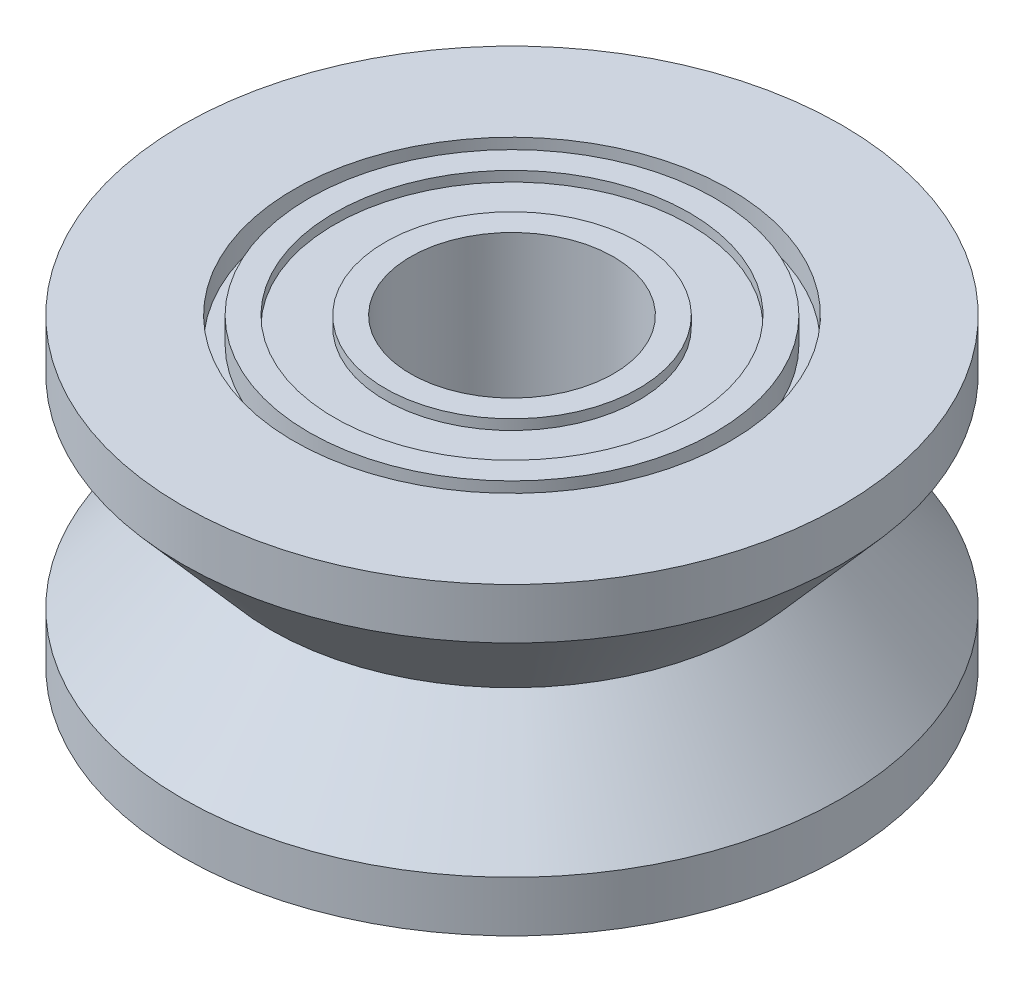
SolidWorks part; units mm, degrees
material "AISI 304"
ref_plane "Front Plane" through (0, 0, 0) normal (0, 0, 1) x (1, 0, 0)
ref_plane "Top Plane" through (0, 0, 0) normal (0, 1, 0) x (1, 0, 0)
ref_plane "Right Plane" through (0, 0, 0) normal (1, 0, 0) x (0, 0, -1)
sketch "Sketch1" plane through (0, 0, 0) normal (0, 0, 1) x (1, 0, 0)
  line L0 (-6.5, 3) -> (-6.5, 2)
  line L1 (-6.5, 2) -> (-4.75, 0)
  line L2 (-4.75, 0) -> (-6.5, -2)
  line L3 (-6.5, -2) -> (-6.5, -3)
  line L4 (-6.5, -3) -> (-2, -3)
  line L5 (-2, -3) -> (-2, 3)
  line L6 (-2, 3) -> (-6.5, 3)
  line L7 (0, 0) -> (0, 6.842) construction
  point P7 (-2, 0)
  dimension "D1" = 6
  dimension "D2" = 4
  dimension "D3" = 6.5
  dimension "D4" = 2
  dimension "D5" = 4.75
revolve "Revolve1" add sketch "Sketch1" angle 360 about L7
sketch "Sketch2" plane through (0, -3, 0) normal (0, -1, 0) x (1, 0, 0)
  circle A0 centre (0, 0) radius 4
  dimension "D1" = 8
extrude "Cut-Extrude-Thin1" cut sketch "Sketch2" against normal blind 0.5 thin
sketch "Sketch3" plane through (0, -3, 0) normal (0, -1, 0) x (1, 0, 0)
  circle A0 centre (0, 0) radius 3.5
  circle A1 centre (0, 0) radius 2.5
  circle A2 centre (0, 0) radius 2 construction
  circle A3 centre (0, 0) radius 4 construction
  dimension "D1" = 0.5
  dimension "D2" = 0.5
extrude "Cut-Extrude1" cut sketch "Sketch3" against normal blind 0.2
mirror "Mirror1" about plane through (0, 0, 0) normal (0, 1, 0) of "Cut-Extrude1", "Cut-Extrude-Thin1"
sketch "Sketch4" plane through (0, 0, 0) normal (0, 1, 0) x (1, 0, 0)
  circle A0 centre (0, 0) radius 4
  dimension "D1" = 8
extrude "Cut-Extrude2" cut sketch "Sketch4" against normal mid plane 0.2
